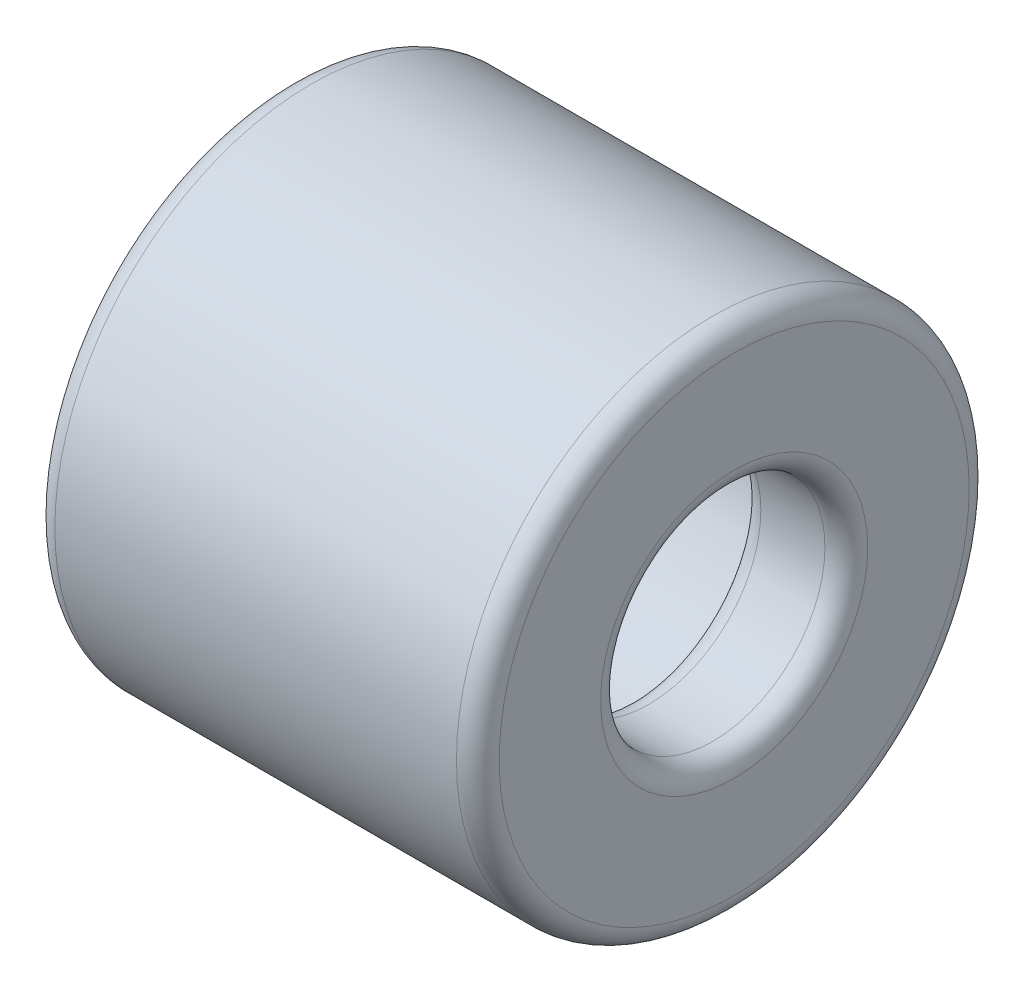
SolidWorks part; units mm, degrees
ref_plane "Front Plane" through (0, 0, 0) normal (0, 0, 1) x (1, 0, 0)
ref_plane "Top Plane" through (0, 0, 0) normal (0, 1, 0) x (1, 0, 0)
ref_plane "Right Plane" through (0, 0, 0) normal (1, 0, 0) x (0, 0, -1)
sketch "Sketch1" plane through (0, 0, 0) normal (0, 0, 1) x (1, 0, 0)
  line L0 (-1.1743, 0) -> (2.2457, 0) construction
  line L1 (11.4, 4) -> (-3.6, 4)
  line L2 (-3.6, 4) -> (-3.6, 6)
  line L3 (-3.6, 6) -> (-14, 6)
  line L4 (-14, 6) -> (-14, 0)
  line L5 (-14, 0) -> (11.4, 0)
  line L6 (11.4, 0) -> (11.4, 4)
  line L7 (3.6, 4.1) -> (3.6, 6)
  line L8 (3.6, 6) -> (14, 6)
  line L9 (14, 6) -> (14, 0)
  line L10 (14, 0) -> (11.5, 0)
  line L11 (11.5, 0) -> (11.5, 4.1)
  line L12 (11.5, 4.1) -> (3.6, 4.1)
  line L13 (-3.6, 6) -> (3.6, 6) construction
  line L14 (0, 0) -> (0, 6) construction
  dimension "D1" = 0.1
  dimension "D2" = 0.1
  dimension "D3" = 7.2
  dimension "D4" = 28
  dimension "D5" = 4
  dimension "D6" = 2
  dimension "D7" = 2.5
revolve "Revolve1" add sketch "Sketch1" angle 360 about L0
sketch "Sketch2" plane through (0, 0, 0) normal (1, 0, 0) x (0, 0, -1)
  circle A0 centre (0, 0) radius 2.625
  dimension "D1" = 5.25
extrude "Cut-Extrude1" cut sketch "Sketch2" against normal through all both and the other way through all
fillet "Fillet1" radius 0.5 5 edges at (14, 0, 6) (14, 0, -2.625) (11.5, 0, 2.625) (3.6, 0, 4.1) (3.6, 0, 6)
